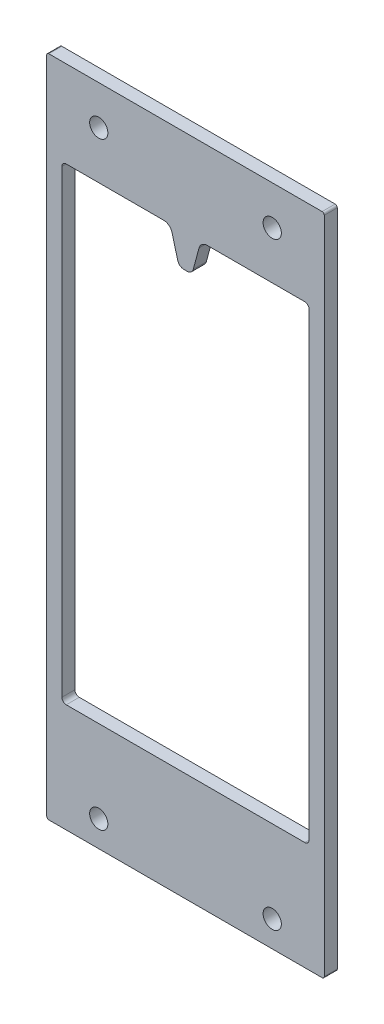
SolidWorks part; units mm, degrees
material "ABS"
ref_plane "Front Plane" through (0, 0, 0) normal (0, 0, 1) x (1, 0, 0)
ref_plane "Top Plane" through (0, 0, 0) normal (0, 1, 0) x (1, 0, 0)
ref_plane "Right Plane" through (0, 0, 0) normal (1, 0, 0) x (0, 0, -1)
sketch "Sketch1" plane through (0, 0, 0) normal (0, 0, 1) x (1, 0, 0)
  line L0 (28.5, 20) -> (28.5, 0) construction
  line L1 (0, 0) -> (23.4557, 0)
  line L2 (0, 0) -> (0, -108)
  line L3 (0, -110) -> (57, -110) construction
  line L4 (57, 0) -> (57, -108)
  line L5 (-3.5, 20) -> (60.5, 20)
  line L6 (-3.5, 20) -> (-3.5, -133)
  line L7 (-3.5, -133) -> (60.5, -133)
  line L8 (60.5, 20) -> (60.5, -133)
  line L9 (-3.5, -58) -> (60.5, -58) construction
  line L12 (33.5443, 0) -> (57, 0)
  line L13 (28.5, -12) -> (28.5, -133) construction
  line L14 (25.3876, -1.4824) -> (26.7021, -6.3882)
  line L15 (28.151, -7.5) -> (28.849, -7.5)
  line L16 (30.2979, -6.3882) -> (31.6124, -1.4824)
  line L17 (0, -108) -> (57, -108)
  circle A0 centre (8.5, 11) radius 2.1
  circle A1 centre (48.5, 11) radius 2.1
  circle A2 centre (48.5, -127) radius 2.1
  circle A3 centre (8.5, -127) radius 2.1
  arc A5 (28.151, -7.5) -> (26.7021, -6.3882) centre (28.151, -6) cw
  arc A6 (28.849, -7.5) -> (30.2979, -6.3882) centre (28.849, -6) ccw
  arc A7 (25.3876, -1.4824) -> (23.4557, 0) centre (23.4557, -2) ccw
  arc A8 (33.5443, 0) -> (31.6124, -1.4824) centre (33.5443, -2) ccw
  point P9 (28.5, -133)
  point P10 (28.5, -110)
  point P11 (28.5, -108)
  point P33 (27, -7.5)
  point P36 (30, -7.5)
  point P39 (24.9904, 0)
  point P42 (32.0096, 0)
  dimension "D11" = 1.5
  dimension "D12" = 1.5
  dimension "D13" = 2
  dimension "D14" = 2
  dimension "D16" = 4.2
  dimension "D1" = 57
  dimension "D2" = 110
  dimension "D3" = 64
  dimension "D4" = 153
  dimension "D5" = 12
  dimension "D6" = 9
  dimension "D7" = 7.5
  dimension "D8" = 3
  dimension "D9" = 105
  dimension "D10" = 105
  dimension "D15" = 25
  dimension "D17" = 6
extrude "Boss-Extrude1" add sketch "Sketch1" along normal blind 3
fillet "Fillet2" radius 0.5 4 edges at (60.5, -133, 1.5) (-3.5, -133, 1.5) (60.5, 20, 1.5) (-3.5, 20, 1.5)
fillet "Fillet3" radius 1 4 edges at (57, 0, 1.5) (0, 0, 1.5) (57, -108, 1.5) (0, -108, 1.5)
equation "\"Depth\"= 90mm"
equation "\"Height\" = 150mm"
equation "\"Width\"= 64mm"
equation "\"D3@Sketch1\"=\"Width\""
equation "\"D4@Sketch1\"=\"Height\" +3"
